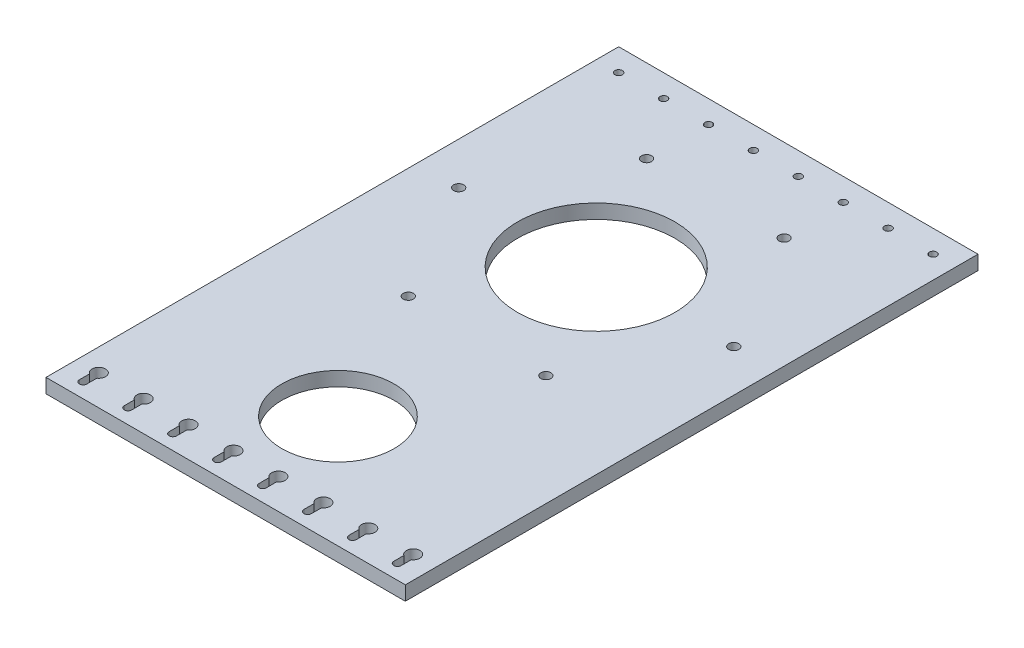
SolidWorks part; units mm, degrees
material "6061 Alloy"
ref_plane "Front Plane" through (0, 0, 0) normal (0, 0, 1) x (1, 0, 0)
ref_plane "Top Plane" through (0, 0, 0) normal (0, 1, 0) x (1, 0, 0)
ref_plane "Right Plane" through (0, 0, 0) normal (1, 0, 0) x (0, 0, -1)
sketch "Sketch1" plane through (0, 0, 0) normal (0, 1, 0) x (1, 0, 0)
  line L0 (80, 255) -> (80, 0) construction
  line L1 (0, 0) -> (160, 0)
  line L2 (0, 0) -> (0, 255)
  line L3 (0, 255) -> (160, 255)
  line L4 (160, 0) -> (160, 255)
  line L5 (80, 165) -> (141.25, 165) construction
  line L6 (10, 6.5) -> (10, 13.5) construction
  line L8 (14.5, 0) -> (14.5, 255) construction
  line L9 (14.5, 131) -> (0, 131) construction
  line L11 (0, 131) -> (0, 121) construction
  line L13 (8.35, 6.5) -> (8.35, 13.5)
  line L14 (11.65, 6.5) -> (11.65, 13.5)
  line L15 (10, 245) -> (10, 0) construction
  line L16 (31.65, 6.5) -> (31.65, 13.5)
  line L17 (28.35, 6.5) -> (28.35, 13.5)
  line L18 (30, 6.5) -> (30, 13.5) construction
  line L19 (51.65, 6.5) -> (51.65, 13.5)
  line L20 (48.35, 6.5) -> (48.35, 13.5)
  line L21 (50, 6.5) -> (50, 13.5) construction
  line L22 (71.65, 6.5) -> (71.65, 13.5)
  line L23 (68.35, 6.5) -> (68.35, 13.5)
  line L24 (70, 6.5) -> (70, 13.5) construction
  line L25 (91.65, 6.5) -> (91.65, 13.5)
  line L26 (88.35, 6.5) -> (88.35, 13.5)
  line L27 (90, 6.5) -> (90, 13.5) construction
  line L28 (111.65, 6.5) -> (111.65, 13.5)
  line L29 (108.35, 6.5) -> (108.35, 13.5)
  line L30 (110, 6.5) -> (110, 13.5) construction
  line L31 (131.65, 6.5) -> (131.65, 13.5)
  line L32 (128.35, 6.5) -> (128.35, 13.5)
  line L33 (130, 6.5) -> (130, 13.5) construction
  line L34 (151.65, 6.5) -> (151.65, 13.5)
  line L35 (148.35, 6.5) -> (148.35, 13.5)
  line L36 (150, 6.5) -> (150, 13.5) construction
  line L37 (10, 245) -> (30, 245) construction
  circle A0 centre (80, 165) radius 35
  circle A1 centre (80, 50) radius 25
  circle A2 centre (80, 165) radius 61.25 construction
  circle A3 centre (141.25, 165) radius 2.25
  circle A4 centre (110.625, 111.9559) radius 2.25
  circle A5 centre (49.375, 111.9559) radius 2.25
  circle A6 centre (18.75, 165) radius 2.25
  circle A7 centre (49.375, 218.0441) radius 2.25
  circle A8 centre (110.625, 218.0441) radius 2.25
  circle A12 centre (80, 165) radius 78 construction
  circle A13 centre (10, 245) radius 1.65
  arc A14 (8.35, 6.5) -> (11.65, 6.5) centre (10, 6.5) ccw
  arc A15 (11.65, 13.5) -> (8.35, 13.5) centre (10, 13.5) ccw
  circle A16 centre (30, 245) radius 1.65
  arc A17 (28.35, 6.5) -> (31.65, 6.5) centre (30, 6.5) ccw
  arc A18 (31.65, 13.5) -> (28.35, 13.5) centre (30, 13.5) ccw
  circle A19 centre (50, 245) radius 1.65
  arc A20 (48.35, 6.5) -> (51.65, 6.5) centre (50, 6.5) ccw
  arc A21 (51.65, 13.5) -> (48.35, 13.5) centre (50, 13.5) ccw
  circle A22 centre (70, 245) radius 1.65
  arc A23 (68.35, 6.5) -> (71.65, 6.5) centre (70, 6.5) ccw
  arc A24 (71.65, 13.5) -> (68.35, 13.5) centre (70, 13.5) ccw
  circle A25 centre (90, 245) radius 1.65
  arc A26 (88.35, 6.5) -> (91.65, 6.5) centre (90, 6.5) ccw
  arc A27 (91.65, 13.5) -> (88.35, 13.5) centre (90, 13.5) ccw
  circle A28 centre (110, 245) radius 1.65
  arc A29 (108.35, 6.5) -> (111.65, 6.5) centre (110, 6.5) ccw
  arc A30 (111.65, 13.5) -> (108.35, 13.5) centre (110, 13.5) ccw
  circle A31 centre (130, 245) radius 1.65
  arc A32 (128.35, 6.5) -> (131.65, 6.5) centre (130, 6.5) ccw
  arc A33 (131.65, 13.5) -> (128.35, 13.5) centre (130, 13.5) ccw
  circle A34 centre (150, 245) radius 1.65
  arc A35 (148.35, 6.5) -> (151.65, 6.5) centre (150, 6.5) ccw
  arc A36 (151.65, 13.5) -> (148.35, 13.5) centre (150, 13.5) ccw
  point P15 (80, 165)
  point P29 (10, 10)
  point P30 (0, 0)
  point P31 (0, 0)
  point P32 (0, 0)
  point P33 (0, 0)
  point P55 (30, 10)
  point P65 (50, 10)
  point P74 (70, 10)
  point P83 (90, 10)
  point P92 (110, 10)
  point P101 (130, 10)
  point P110 (150, 10)
  dimension "D3" = 70
  dimension "D4" = 50
  dimension "D7" = 122.5
  dimension "D8" = 4.5
  dimension "D11" = 124
  dimension "D16" = 156
  dimension "D19" = 3.3
  dimension "D24" = 235
  dimension "D1" = 160
  dimension "D2" = 255
  dimension "D5" = 115
  dimension "D6" = 90
  dimension "D10" = 61.25
  dimension "D12" = 65.5
  dimension "D18" = 80
  dimension "D20" = 10
  dimension "D21" = 10
  dimension "D22" = 3.3
  dimension "D23" = 7
  dimension "D26" = 20
  dimension "D25" = 8
  dimension "D9" = 6
extrude "Boss-Extrude1" add sketch "Sketch1" along normal blind 6.35 contours A1 | A0 | A4 | A8 | A7 | A6
sketch "Sketch2" plane through (0, 6.35, 0) normal (0, 1, 0) x (1, 0, 0)
  line L0 (150, 13.5) -> (130, 13.5) construction
  circle A8 centre (150, 13.5) radius 3
  circle A9 centre (130, 13.5) radius 3
  circle A10 centre (110, 13.5) radius 3
  circle A11 centre (90, 13.5) radius 3
  circle A12 centre (70, 13.5) radius 3
  circle A13 centre (50, 13.5) radius 3
  circle A14 centre (30, 13.5) radius 3
  circle A15 centre (10, 13.5) radius 3
  dimension "D1" = 6
  dimension "D2" = 8
  dimension "D3" = 20
extrude "Cut-Extrude1" cut sketch "Sketch2" against normal up to next
